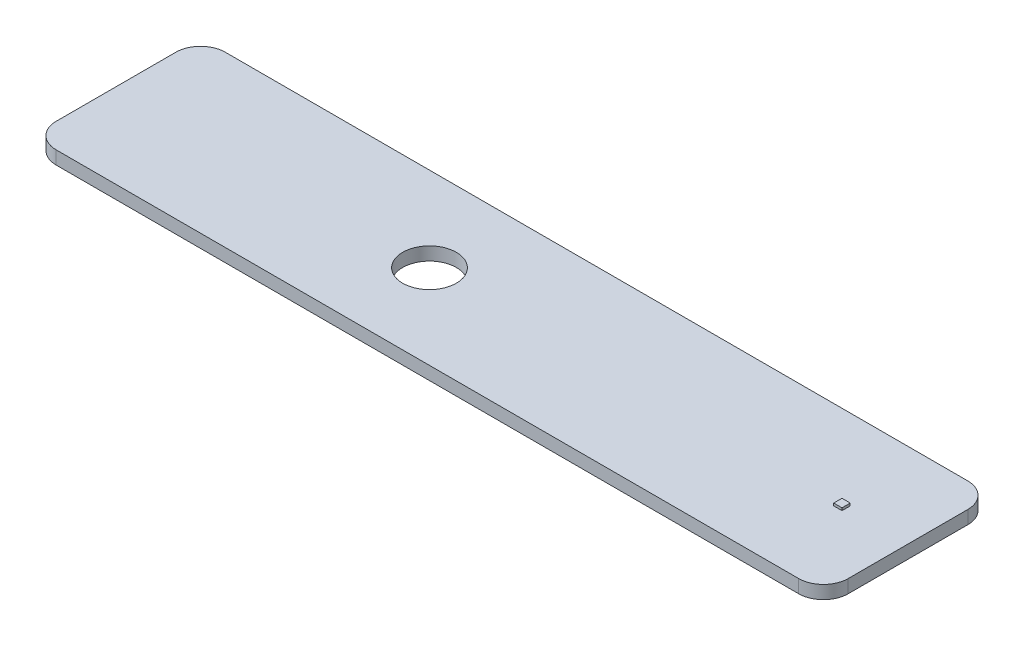
SolidWorks part; units mm, degrees
material "Custom Plastic"
ref_plane "Front Plane" through (0, 0, 0) normal (0, 0, 1) x (1, 0, 0)
ref_plane "Top Plane" through (0, 0, 0) normal (0, 1, 0) x (1, 0, 0)
ref_plane "Right Plane" through (0, 0, 0) normal (1, 0, 0) x (0, 0, -1)
sketch "Sketch1" plane through (0, 0, 0) normal (0, 1, 0) x (1, 0, 0)
  line L1 (-45, 10.25) -> (45, 10.25)
  line L2 (-48, 7.25) -> (-48, -7.25)
  line L3 (-45, -10.25) -> (45, -10.25)
  line L4 (48, 7.25) -> (48, -7.25)
  line L5 (-48, 10.25) -> (48, -10.25) construction
  line L6 (-48, -10.25) -> (48, 10.25) construction
  arc A0 (-48, -7.25) -> (-45, -10.25) centre (-45, -7.25) ccw
  arc A1 (45, -10.25) -> (48, -7.25) centre (45, -7.25) ccw
  arc A2 (45, 10.25) -> (48, 7.25) centre (45, 7.25) cw
  arc A3 (-45, 10.25) -> (-48, 7.25) centre (-45, 7.25) ccw
  point P0 (0, 0)
  dimension "D3" = 3
  dimension "D1" = 96
  dimension "D2" = 20.5
extrude "Boss-Extrude1" add sketch "Sketch1" along normal blind 1.6 contours L3 A1 L4 A2 L1 A3 L2 A0
sketch "Sketch2" plane through (0, 1.6, 0) normal (0, 1, 0) x (1, 0, 0)
  line L1 (39.5, 0.5) -> (40.5, 0.5)
  line L2 (39.5, 0.5) -> (39.5, -0.5)
  line L3 (39.5, -0.5) -> (40.5, -0.5)
  line L4 (40.5, 0.5) -> (40.5, -0.5)
  line L5 (39.5, 0.5) -> (40.5, -0.5) construction
  line L6 (39.5, -0.5) -> (40.5, 0.5) construction
  line L7 (-48, 0) -> (48, 0) construction
  line L8 (-48, 7.25) -> (-48, -7.25) construction
  line L9 (48, 7.25) -> (48, -7.25) construction
  point P0 (40, 0)
  dimension "D1" = 1
  dimension "D2" = 1
  dimension "D3" = 88
extrude "Boss-Extrude2" add sketch "Sketch2" along normal blind 0.3 contours L3 L4 L1 L2
sketch "Sketch3" plane through (0, 1.6, 0) normal (0, 1, 0) x (1, 0, 0)
  line L0 (-48, 7.25) -> (-48, -7.25) construction
  line L2 (-45, -10.25) -> (45, -10.25) construction
  circle A0 centre (-10, 0) radius 3.25
  dimension "D1" = 6.5
  dimension "D2" = 38
  dimension "D3" = 10.25
extrude "Cut-Extrude1" cut sketch "Sketch3" against normal through all
